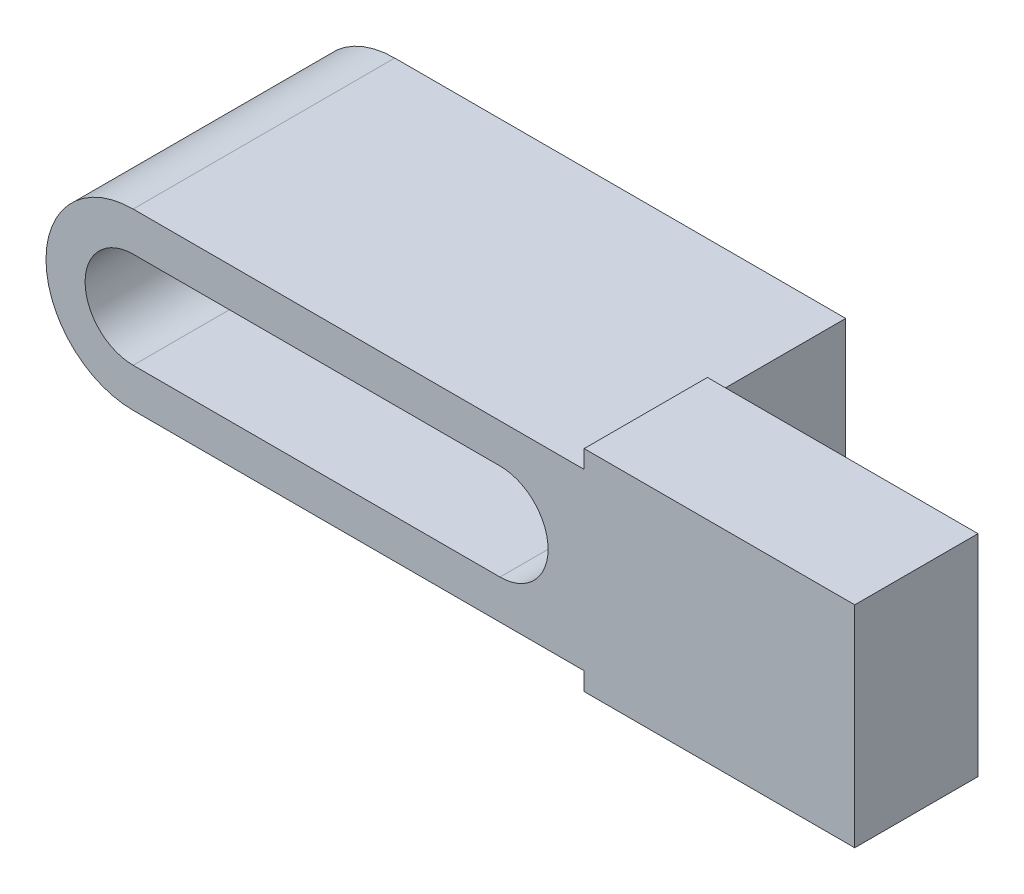
SolidWorks part; units mm, degrees
ref_plane "Спереди" through (0, 0, 0) normal (0, 0, 1) x (1, 0, 0)
ref_plane "Сверху" through (0, 0, 0) normal (0, 1, 0) x (1, 0, 0)
ref_plane "Справа" through (0, 0, 0) normal (1, 0, 0) x (0, 0, -1)
sketch "Эскиз1" plane through (0, 0, 0) normal (0, 0, 1) x (1, 0, 0)
  line L0 (0, 2.9) -> (15, 2.9)
  line L1 (15, 2.9) -> (15, -2.9)
  line L2 (15, -2.9) -> (0, -2.9)
  arc A0 (0, 2.9) -> (0, -2.9) centre (0, 0) ccw
  dimension "D1" = 5.8
  dimension "D2" = 15
extrude "Бобышка-Вытянуть1" add sketch "Эскиз1" along normal blind 4.6
sketch "Эскиз2" plane through (0, 0, 4.6) normal (0, 0, 1) x (1, 0, 0)
  line L0 (24, 3.5) -> (24, -3.5)
  line L2 (15, 2.9) -> (15, 3.5)
  line L3 (0, -2.9) -> (15, -2.9)
  line L4 (15, -2.9) -> (15, 2.9)
  line L5 (15, 2.9) -> (0, 2.9)
  line L6 (0, -2.9) -> (15, -2.9)
  line L8 (15, 2.9) -> (0, 2.9)
  line L9 (15, 3.5) -> (24, 3.5)
  line L10 (15, -2.9) -> (15, -3.5)
  line L11 (15, -3.5) -> (24, -3.5)
  arc A1 (0, 2.9) -> (0, -2.9) centre (0, 0) ccw
  arc A2 (0, 2.9) -> (0, -2.9) centre (0, 0) ccw
  dimension "D2" = 24
  dimension "D3" = 7
  dimension "D4" = 9
  dimension "D1" = 0
extrude "Бобышка-Вытянуть2" add sketch "Эскиз2" along normal blind 4.1
sketch "Эскиз3" plane through (0, 0, 8.7) normal (0, 0, 1) x (1, 0, 0)
  line L0 (15, -2.9) -> (15, 2.9) construction
  line L1 (0, 1.6) -> (12.2, 1.6)
  line L2 (12.2, -1.6) -> (0, -1.6)
  arc A0 (0, 1.6) -> (0, -1.6) centre (0, 0) ccw
  arc A1 (12.2, -1.6) -> (12.2, 1.6) centre (12.2, 0) ccw
  dimension "D1" = 3.2
  dimension "D2" = 3.2
  dimension "D3" = 2.8
extrude "Вырез-Вытянуть1" cut sketch "Эскиз3" against normal through all
